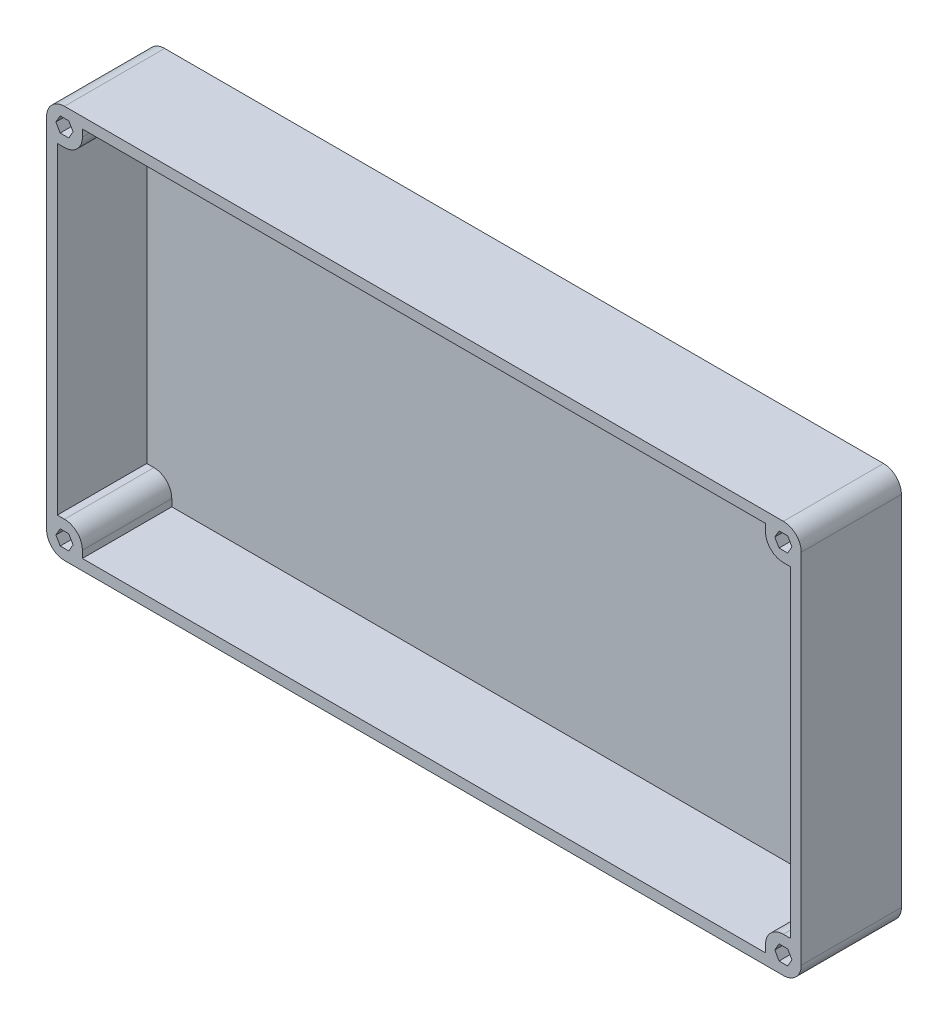
SolidWorks part; units mm, degrees
ref_plane "Front Plane" through (0, 0, 0) normal (0, 0, 1) x (1, 0, 0)
ref_plane "Top Plane" through (0, 0, 0) normal (0, 1, 0) x (1, 0, 0)
ref_plane "Right Plane" through (0, 0, 0) normal (1, 0, 0) x (0, 0, -1)
sketch "Sketch1" plane through (0, 0, 0) normal (0, 0, 1) x (1, 0, 0)
  line L1 (6.35, 0) -> (261.62, 0)
  line L2 (0, 6.35) -> (0, 133.35)
  line L3 (6.35, 139.7) -> (261.62, 139.7)
  line L4 (267.97, 6.35) -> (267.97, 133.35)
  arc A0 (6.35, 0) -> (0, 6.35) centre (6.35, 6.35) cw
  arc A1 (261.62, 0) -> (267.97, 6.35) centre (261.62, 6.35) ccw
  arc A2 (261.62, 139.7) -> (267.97, 133.35) centre (261.62, 133.35) cw
  arc A3 (0, 133.35) -> (6.35, 139.7) centre (6.35, 133.35) cw
  point P7 (0, 0)
  point P10 (267.97, 0)
  point P15 (0, 139.7)
  dimension "D3" = 6.35
  dimension "D1" = 139.7
  dimension "10.55" = 267.97
extrude "Boss-Extrude1" add sketch "Sketch1" along normal blind 35.56
shell "Shell1" thickness 3.81
sketch "Sketch2" plane through (0, 0, 35.56) normal (0, 0, 1) x (1, 0, 0)
  line L0 (261.62, 139.7) -> (6.35, 139.7) construction
  line L1 (0, 133.35) -> (0, 6.35) construction
  line L2 (255.27, 139.7) -> (261.62, 139.7)
  line L3 (267.97, 127) -> (267.97, 133.35)
  line L4 (12.7, 133.35) -> (12.7, 139.7)
  line L5 (6.35, 127) -> (0, 127)
  line L6 (0, 127) -> (0, 133.35)
  line L7 (12.7, 139.7) -> (6.35, 139.7)
  line L8 (133.985, 139.7) -> (133.985, 122.7569) construction
  line L9 (6.35, 0) -> (261.62, 0) construction
  line L10 (261.62, 127) -> (267.97, 127)
  line L11 (255.27, 133.35) -> (255.27, 139.7)
  line L12 (12.7, 0) -> (6.35, 0)
  line L13 (0, 12.7) -> (0, 6.35)
  line L14 (6.35, 12.7) -> (0, 12.7)
  line L15 (12.7, 6.35) -> (12.7, 0)
  line L16 (255.27, 6.35) -> (255.27, 0)
  line L17 (261.62, 12.7) -> (267.97, 12.7)
  line L18 (267.97, 12.7) -> (267.97, 6.35)
  line L19 (255.27, 0) -> (261.62, 0)
  circle A0 centre (6.35, 133.35) radius 1.5875
  arc A8 (6.35, 139.7) -> (0, 133.35) centre (6.35, 133.35) ccw
  arc A9 (6.35, 127) -> (12.7, 133.35) centre (6.35, 133.35) ccw
  arc A10 (261.62, 127) -> (255.27, 133.35) centre (261.62, 133.35) cw
  arc A11 (261.62, 139.7) -> (267.97, 133.35) centre (261.62, 133.35) cw
  circle A12 centre (261.62, 133.35) radius 1.5875
  arc A13 (6.35, 12.7) -> (12.7, 6.35) centre (6.35, 6.35) cw
  arc A14 (6.35, 0) -> (0, 6.35) centre (6.35, 6.35) cw
  circle A15 centre (6.35, 6.35) radius 1.5875
  circle A16 centre (261.62, 6.35) radius 1.5875
  arc A17 (261.62, 0) -> (267.97, 6.35) centre (261.62, 6.35) ccw
  arc A18 (261.62, 12.7) -> (255.27, 6.35) centre (261.62, 6.35) ccw
  dimension "D1" = 3.175
  dimension "D2" = 6.35
  dimension "D5" = 6.35
  dimension "D6" = 6.35
extrude "Boss-Extrude2" add sketch "Sketch2" against normal through all
sketch "Sketch3" plane through (0, 0, 35.56) normal (0, 0, 1) x (1, 0, 0)
  line L1 (9.398, 133.35) -> (7.874, 135.9896)
  line L2 (7.874, 135.9896) -> (4.826, 135.9896)
  line L3 (4.826, 135.9896) -> (3.302, 133.35)
  line L4 (3.302, 133.35) -> (4.826, 130.7104)
  line L5 (4.826, 130.7104) -> (7.874, 130.7104)
  line L6 (7.874, 130.7104) -> (9.398, 133.35)
  line L7 (258.572, 133.35) -> (260.096, 130.7104)
  line L8 (260.096, 130.7104) -> (263.144, 130.7104)
  line L9 (263.144, 130.7104) -> (264.668, 133.35)
  line L10 (264.668, 133.35) -> (263.144, 135.9896)
  line L11 (263.144, 135.9896) -> (260.096, 135.9896)
  line L12 (260.096, 135.9896) -> (258.572, 133.35)
  line L13 (264.668, 6.35) -> (263.144, 8.9896)
  line L14 (263.144, 8.9896) -> (260.096, 8.9896)
  line L15 (260.096, 8.9896) -> (258.572, 6.35)
  line L16 (258.572, 6.35) -> (260.096, 3.7104)
  line L17 (260.096, 3.7104) -> (263.144, 3.7104)
  line L18 (263.144, 3.7104) -> (264.668, 6.35)
  line L19 (9.398, 6.35) -> (7.874, 8.9896)
  line L20 (7.874, 8.9896) -> (4.826, 8.9896)
  line L21 (4.826, 8.9896) -> (3.302, 6.35)
  line L22 (3.302, 6.35) -> (4.826, 3.7104)
  line L23 (4.826, 3.7104) -> (7.874, 3.7104)
  line L24 (7.874, 3.7104) -> (9.398, 6.35)
  circle A0 centre (6.35, 133.35) radius 2.6396 construction
  circle A1 centre (261.62, 133.35) radius 2.6396 construction
  circle A2 centre (261.62, 6.35) radius 2.6396 construction
  circle A3 centre (6.35, 6.35) radius 2.6396 construction
  dimension "D1" = 6.096
  dimension "D2" = 6.096
  dimension "D3" = 6.096
  dimension "D4" = 6.096
extrude "Cut-Extrude1" cut sketch "Sketch3" against normal blind 5.08
